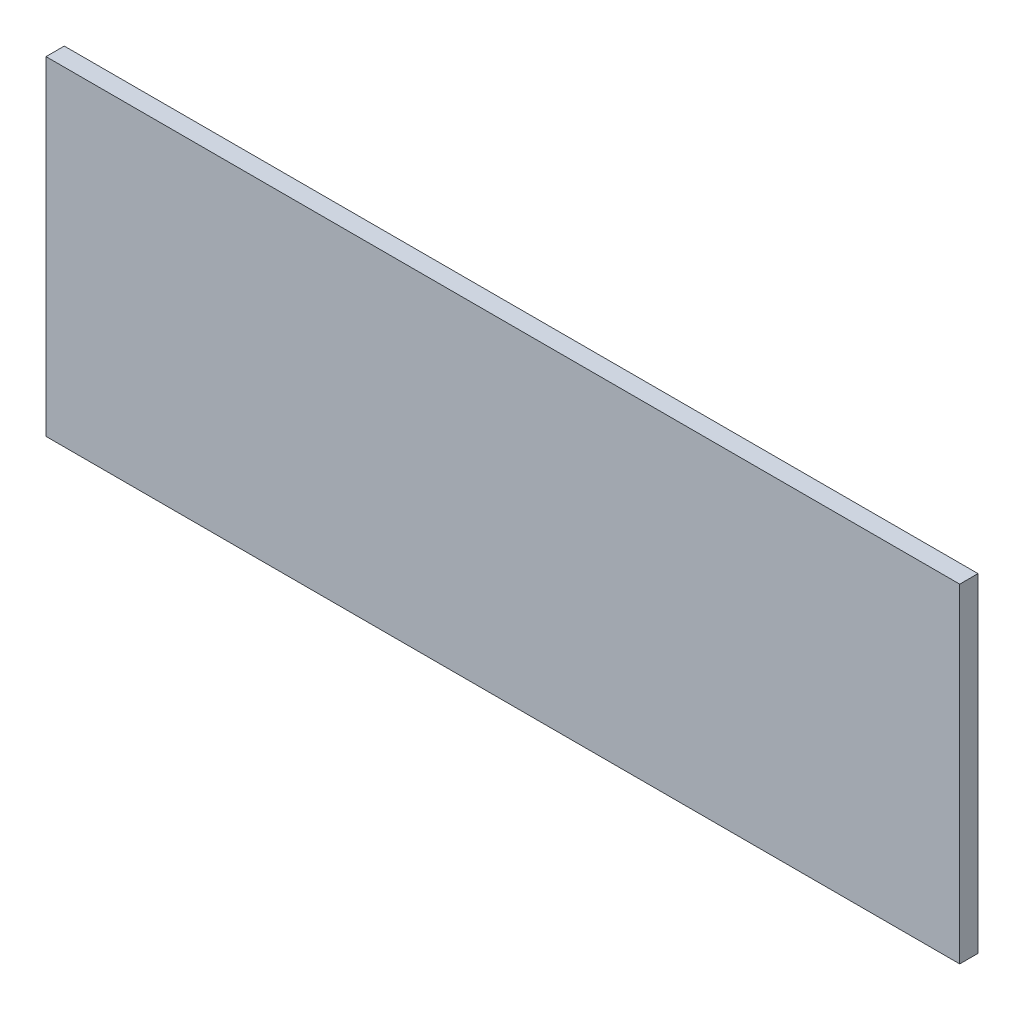
SolidWorks part; units mm, degrees
ref_plane "Front Plane" through (0, 0, 0) normal (0, 0, 1) x (1, 0, 0)
ref_plane "Top Plane" through (0, 0, 0) normal (0, 1, 0) x (1, 0, 0)
ref_plane "Right Plane" through (0, 0, 0) normal (1, 0, 0) x (0, 0, -1)
sketch "Sketch1" plane through (0, 0, 0) normal (0, 0, 1) x (1, 0, 0)
  line L1 (125, -45) -> (-125, -45)
  line L2 (125, -45) -> (125, 45)
  line L3 (125, 45) -> (-125, 45)
  line L4 (-125, -45) -> (-125, 45)
  line L5 (125, -45) -> (-125, 45) construction
  line L6 (125, 45) -> (-125, -45) construction
  point P1 (0, 0)
  dimension "D1" = 250
  dimension "D2" = 90
extrude "Boss-Extrude1" add sketch "Sketch1" along normal blind 5
